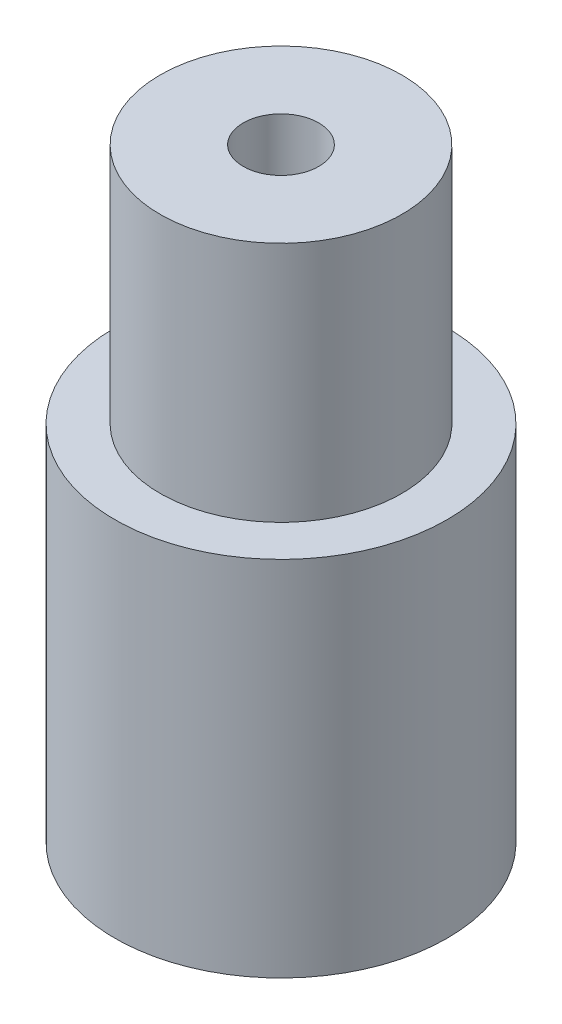
SolidWorks part; units mm, degrees
material "PE(聚乙烯)"
ref_plane "前视" through (0, 0, 0) normal (0, 0, 1) x (1, 0, 0)
ref_plane "上视" through (0, 0, 0) normal (0, 1, 0) x (1, 0, 0)
ref_plane "右视" through (0, 0, 0) normal (1, 0, 0) x (0, 0, -1)
sketch "草图1" plane through (0, 0, 0) normal (0, 0, 1) x (1, 0, 0)
  line L0 (0, 0) -> (0, -10)
  line L1 (0, 0) -> (4, 0)
  line L2 (4, 0) -> (4, -8)
  line L3 (4, -8) -> (5.5, -8)
  line L4 (5.5, -8) -> (5.5, -20)
  line L5 (5.5, -20) -> (0.5, -20)
  line L6 (0.5, -20) -> (0.5, -10)
  line L7 (0.5, -10) -> (0, -10)
  line L8 (0, 0) -> (0, -17.2441) construction
  dimension "D1" = 8
  dimension "D2" = 8
  dimension "D3" = 12
  dimension "D4" = 11
  dimension "D5" = 1
  dimension "D6" = 10
revolve "旋转1" add sketch "草图1" angle 360 about L8
hole_wizard "M3 螺纹孔1" positions "草图3" profile "草图2" tap size "M3" standard "GB"
sketch "草图3" plane through (0, 0, 0) normal (0, 1, 0) x (1, 0, 0)
  point P0 (0, 0)
sketch "草图2" plane through (0, 0, 0) normal (1, 0, 0) x (0, 0, 1)
  line L0 (0, 0) -> (0, 8)
  line L1 (0, 8) -> (1.25, 7.2489)
  line L2 (1.25, 7.2489) -> (1.25, 0)
  line L5 (1.25, 0) -> (0, 0)
  line L10 (0, 8) -> (-1.25, 7.2489) construction
  line L11 (0, -6.35) -> (0, 107.95) construction
  dimension "螺纹孔钻头直径" = 2.5
  dimension "螺纹孔钻头深度" = 8
  dimension "导头角度" = 118
cosmetic thread "孔螺蚊线3"
ref_plane "基准面1" through (-5.5, 0, 0) normal (-1, 0, 0) x (0, 0, 1)
hole_wizard "M3 螺纹孔2" positions "草图6" profile "草图5" tap size "M3" standard "GB"
sketch "草图6" plane through (-5.5, 0, 0) normal (-1, 0, 0) x (0, 0, 1)
  line L0 (-5.5, -20) -> (5.5, -20) construction
  line L1 (0, 0) -> (0, -20) construction
  point P0 (0, -16)
  dimension "D1" = 4
sketch "草图5" plane through (-5.5, -16, 0) normal (0, 1, 0) x (0, 0, 1)
  line L0 (0, 0) -> (0, 5)
  line L1 (0, 5) -> (1.25, 5)
  line L2 (1.25, 5) -> (1.25, 0)
  line L5 (1.25, 0) -> (0, 0)
  line L11 (0, -6.35) -> (0, 107.95) construction
  dimension "通孔螺纹孔钻头直径" = 2.5
  dimension "通孔螺纹孔钻头深度" = 5
cosmetic thread "孔螺蚊线2"
sketch "草图7" plane through (0, -20, 0) normal (0, -1, 0) x (1, 0, 0)
  line L0 (-1, 1.118) -> (-1, -1.118)
  arc A0 (-1, -1.118) -> (-1, 1.118) centre (0, 0) ccw
  dimension "D1" = 1.5
  dimension "D2" = 1
extrude "切除-拉伸1" cut sketch "草图7" against normal blind 10
